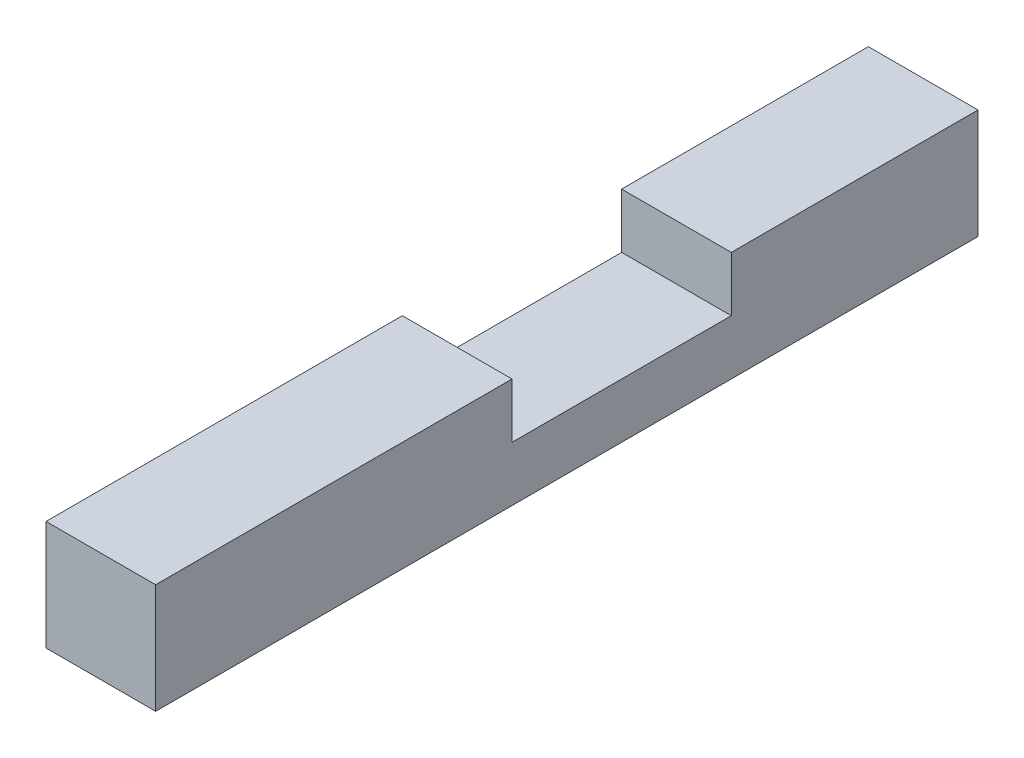
SolidWorks part; units mm, degrees
ref_plane "前基準面" through (0, 0, 0) normal (0, 0, 1) x (1, 0, 0)
ref_plane "上基準面" through (0, 0, 0) normal (0, 1, 0) x (1, 0, 0)
ref_plane "右基準面" through (0, 0, 0) normal (1, 0, 0) x (0, 0, -1)
sketch "草圖1" plane through (0, 0, 0) normal (0, 0, 1) x (1, 0, 0)
  line L1 (-2, 2) -> (2, 2)
  line L2 (-2, 2) -> (-2, -2)
  line L3 (-2, -2) -> (2, -2)
  line L4 (2, 2) -> (2, -2)
  line L5 (-2, 2) -> (2, -2) construction
  line L6 (-2, -2) -> (2, 2) construction
  point P0 (0, 0)
extrude "填料-伸長1" add sketch "草圖1" along normal blind 30 contours L1 L4 L3 L2
sketch "草圖3" plane through (-2, 0, 0) normal (-1, 0, 0) x (0, 0, 1)
  line L0 (30, -2) -> (0, -2) construction
  line L1 (0, 2) -> (9, 2)
  line L2 (0, 2) -> (0, -2)
  line L3 (0, -2) -> (9, -2)
  line L4 (9, 2) -> (9, -2)
sketch "草圖4" plane through (-2, 0, 0) normal (-1, 0, 0) x (0, 0, 1)
  line L1 (9, 2) -> (17, 2)
  line L2 (9, 2) -> (9, 0)
  line L3 (9, 0) -> (17, 0)
  line L4 (17, 2) -> (17, 0)
extrude "除料-伸長1" cut sketch "草圖4" against normal blind 4
